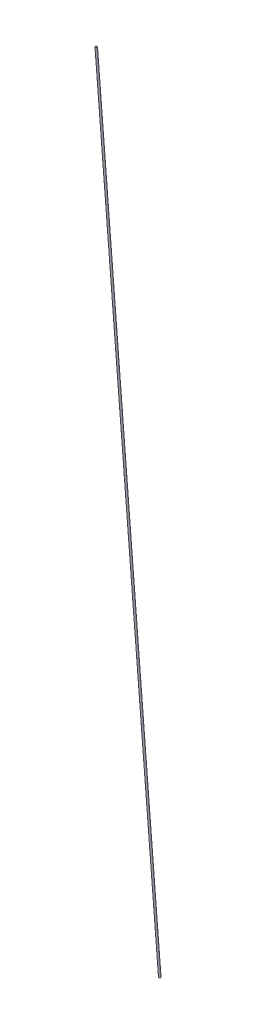
SolidWorks part; units mm, degrees
ref_plane "Front Plane" through (0, 0, 0) normal (0, 0, 1) x (1, 0, 0)
ref_plane "Top Plane" through (0, 0, 0) normal (0, 1, 0) x (1, 0, 0)
ref_plane "Right Plane" through (0, 0, 0) normal (1, 0, 0) x (0, 0, -1)
sketch "Sketch1" plane through (0, 0, 0) normal (0, 0, 1) x (1, 0, 0)
  line L0 (0, 0) -> (0, -1718) construction
  line L1 (0, -1718) -> (141, -1718) construction
  line L2 (0, 0) -> (141, -1718)
  dimension "D1" = 1718
  dimension "D2" = 141
sketch "Sketch2" plane through (0, 0, 0) normal (0, 1, 0) x (1, 0, 0)
  circle A0 centre (0, 0) radius 2
  dimension "D1" = 4
sweep "Sweep2" add profiles "Sketch2" path "Sketch1"
